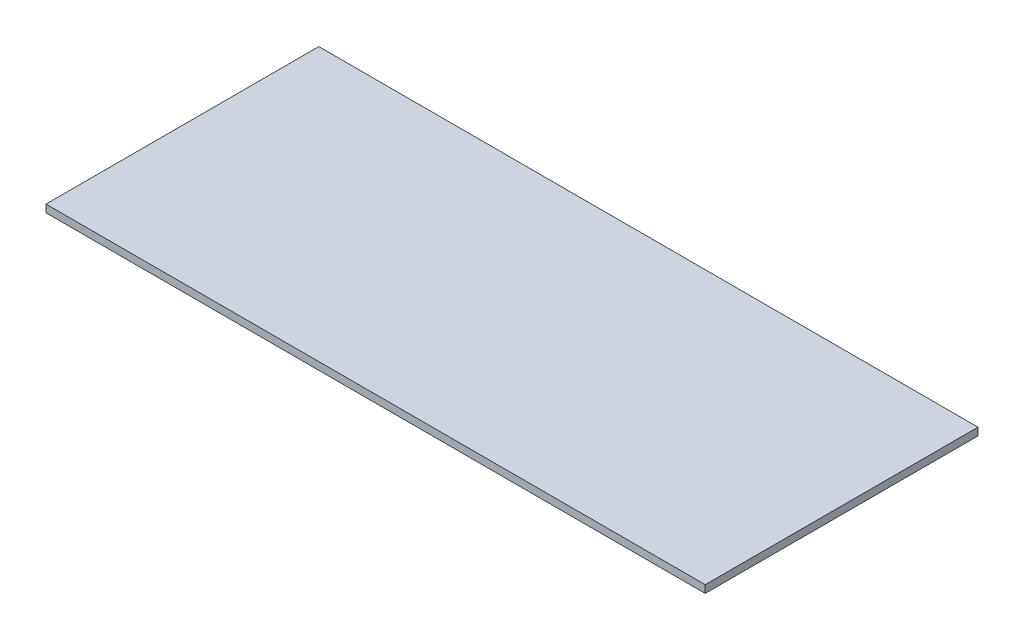
SolidWorks part; units mm, degrees
ref_plane "Front Plane" through (0, 0, 0) normal (0, 0, 1) x (1, 0, 0)
ref_plane "Top Plane" through (0, 0, 0) normal (0, 1, 0) x (1, 0, 0)
ref_plane "Right Plane" through (0, 0, 0) normal (1, 0, 0) x (0, 0, -1)
sketch "Sketch1" plane through (0, 0, 0) normal (0, 1, 0) x (1, 0, 0)
  line L1 (-87, -36) -> (87, -36)
  line L2 (-87, -36) -> (-87, 36)
  line L3 (-87, 36) -> (87, 36)
  line L4 (87, -36) -> (87, 36)
  line L5 (-87, -36) -> (87, 36) construction
  line L6 (-87, 36) -> (87, -36) construction
  point P0 (0, 0)
  dimension "D1" = 174
  dimension "D2" = 72
extrude "Boss-Extrude1" add sketch "Sketch1" along normal mid plane 2
